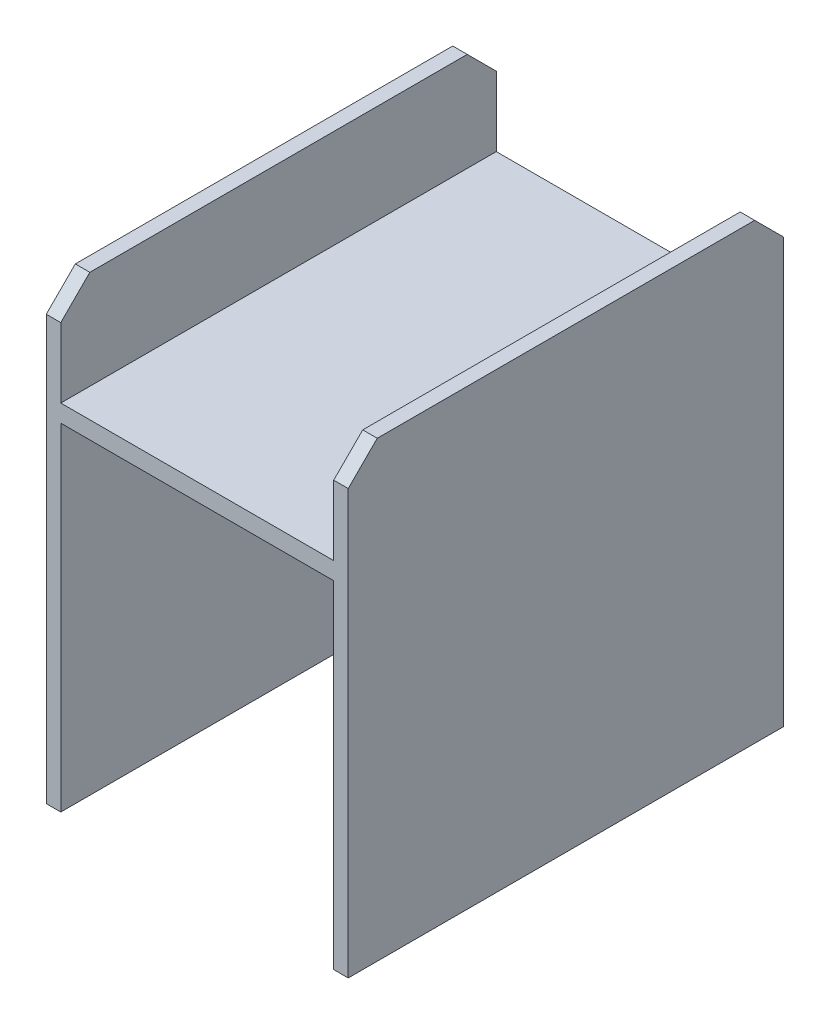
SolidWorks part; units mm, degrees
ref_plane "Front Plane" through (0, 0, 0) normal (0, 0, 1) x (1, 0, 0)
ref_plane "Top Plane" through (0, 0, 0) normal (0, 1, 0) x (1, 0, 0)
ref_plane "Right Plane" through (0, 0, 0) normal (1, 0, 0) x (0, 0, -1)
sketch "Sketch1" plane through (0, 0, 0) normal (0, 1, 0) x (1, 0, 0)
  line L1 (-33.0526, 32.4561) -> (18.9474, 32.4561)
  line L2 (-33.0526, 32.4561) -> (-33.0526, -42.5439)
  line L3 (-33.0526, -42.5439) -> (18.9474, -42.5439)
  line L4 (18.9474, 32.4561) -> (18.9474, -42.5439)
  dimension "D1" = 52
  dimension "D2" = 75
extrude "Boss-Extrude1" add sketch "Sketch1" along normal blind 3
sketch "Sketch2" plane through (0, 3, 0) normal (0, 1, 0) x (1, 0, 0)
  line L0 (-33.0526, -42.5439) -> (18.9474, -42.5439) construction
  line L1 (-33.0526, 32.4561) -> (-30.5526, 32.4561)
  line L2 (-33.0526, 32.4561) -> (-33.0526, -42.5439)
  line L3 (-33.0526, -42.5439) -> (-30.5526, -42.5439)
  line L4 (-30.5526, 32.4561) -> (-30.5526, -42.5439)
  line L6 (18.9474, 32.4561) -> (16.4474, 32.4561)
  line L7 (18.9474, 32.4561) -> (18.9474, -42.5439)
  line L8 (18.9474, -42.5439) -> (16.4474, -42.5439)
  line L9 (16.4474, 32.4561) -> (16.4474, -42.5439)
  dimension "D1" = 2.5
  dimension "D2" = 2.5
extrude "Boss-Extrude2" add sketch "Sketch2" along normal blind 38 and the other way blind 40
sketch "Sketch5" plane through (-30.5526, 0, 0) normal (1, 0, 0) x (0, 0, -1)
  line L0 (-42.5439, 41) -> (-42.5439, -37) construction
  line L1 (-42.5439, 24) -> (32.4561, 24)
  line L2 (-42.5439, 24) -> (-42.5439, 21)
  line L3 (-42.5439, 21) -> (32.4561, 21)
  line L4 (32.4561, 24) -> (32.4561, 21)
  line L5 (32.4561, 41) -> (32.4561, -37) construction
  line L6 (-42.5439, -37) -> (32.4561, -37) construction
  dimension "D1" = 3
  dimension "D2" = 58
extrude "Boss-Extrude5" add sketch "Sketch5" along normal up to surface (47 mm away) up to face at (16.4474, 22, 5.0439)
sketch "Sketch6" plane through (0, 0, 42.5439) normal (0, 0, 1) x (1, 0, 0)
  line L0 (28.6, 0) -> (-28.6, 0) construction
  line L1 (-30.5526, 3) -> (16.4474, 3)
  line L2 (-30.5526, 3) -> (-30.5526, 0)
  line L3 (-30.5526, 0) -> (16.4474, 0)
  line L4 (16.4474, 3) -> (16.4474, 0)
  line L5 (16.4474, -37) -> (16.4474, 0) construction
extrude "Cut-Extrude1" cut sketch "Sketch6" against normal through all both and the other way through all
chamfer "Chamfer1" distance 5 angle 45 4 edges at (17.6974, 41, 42.5439) (-31.8026, 41, -32.4561) (17.6974, 41, -32.4561) (-31.8026, 41, 42.5439)
